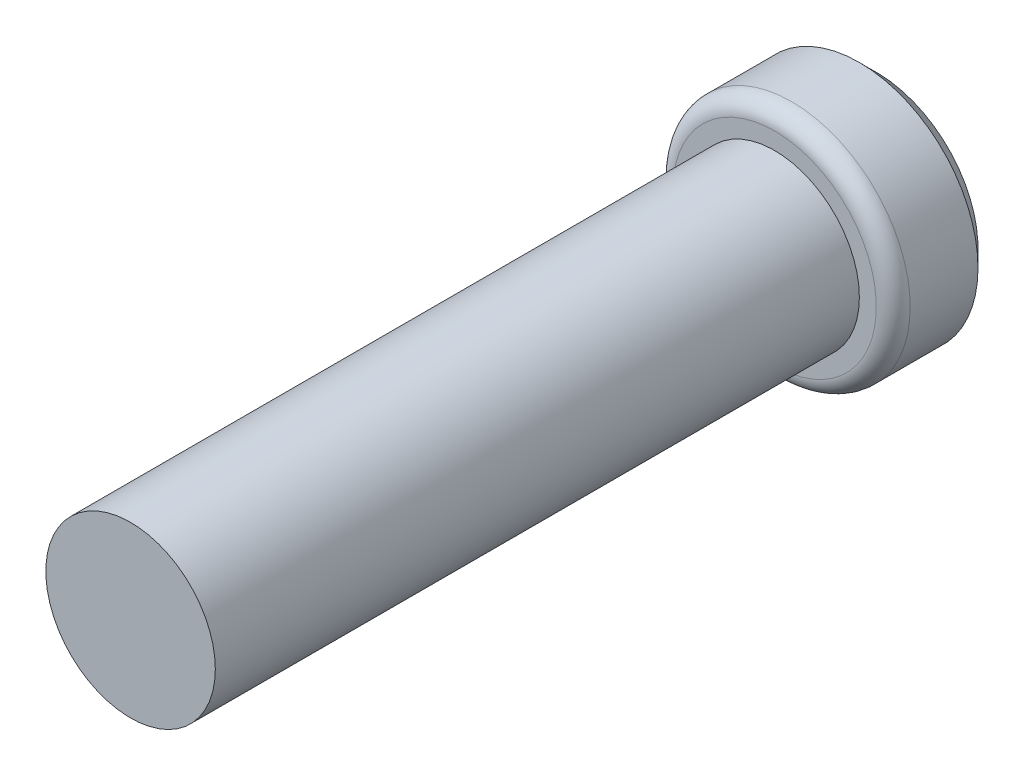
SolidWorks part; units mm, degrees
ref_plane "Front Plane" through (0, 0, 0) normal (0, 0, 1) x (1, 0, 0)
ref_plane "Top Plane" through (0, 0, 0) normal (0, 1, 0) x (1, 0, 0)
ref_plane "Right Plane" through (0, 0, 0) normal (1, 0, 0) x (0, 0, -1)
sketch "Sketch1" plane through (0, 0, 0) normal (0, 0, 1) x (1, 0, 0)
  circle A0 centre (0, 0) radius 4
  circle A1 centre (0, 0) radius 2.5
  dimension "D1" = 5
  dimension "D2" = 8
extrude "Boss-Extrude2" add sketch "Sketch1" along normal blind 19 contours A1
sketch "Sketch2" plane through (0, 0, 0) normal (0, 0, -1) x (-1, 0, 0)
  circle A0 centre (0, 0) radius 3.5
  dimension "D1" = 7
extrude "Boss-Extrude3" add sketch "Sketch2" along normal blind 3
sketch "Sketch4" plane through (0, 0, -3) normal (0, 0, -1) x (-1, 0, 0)
  line L0 (0, 2.5173) -> (0, -2.5173)
  line L1 (2.5173, 0) -> (-2.5173, 0)
  line L3 (0, 2.5173) -> (-2.1801, 1.2587)
  line L4 (-2.1801, 1.2587) -> (-2.1801, -1.2587)
  line L5 (-2.1801, -1.2587) -> (0, -2.5173)
  line L6 (0, -2.5173) -> (2.1801, -1.2587)
  line L7 (2.1801, -1.2587) -> (2.1801, 1.2587)
  line L8 (2.1801, 1.2587) -> (0, 2.5173)
  circle A0 centre (0, 0) radius 2.5173
  circle A1 centre (0, 0) radius 2.1801 construction
extrude "Cut-Extrude2" cut sketch "Sketch4" against normal blind 2 contours L6 L7 L1 L0 | L7 L8 L0 L1 | L3 L4 L1 L0 | L4 L5 L0 L1
chamfer "Chamfer2" distance 0.5 angle 45 1 edges at (-3.5, 0, -3)
fillet "Fillet5" radius 0.5 1 edges at (-3.5, 0, 0)
